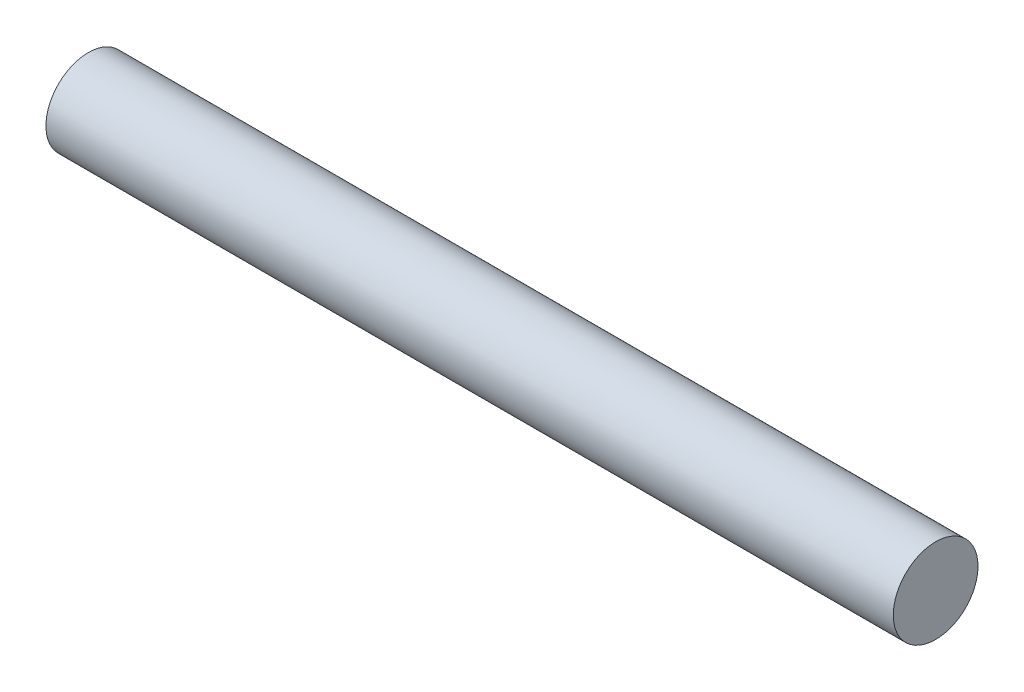
SolidWorks part; units mm, degrees
material "Stainless Steel (ferritic)"
ref_plane "Front Plane" through (0, 0, 0) normal (0, 0, 1) x (1, 0, 0)
ref_plane "Top Plane" through (0, 0, 0) normal (0, 1, 0) x (1, 0, 0)
ref_plane "Right Plane" through (0, 0, 0) normal (1, 0, 0) x (0, 0, -1)
sketch "Sketch1" plane through (0, 0, 0) normal (1, 0, 0) x (0, 0, -1)
  circle A0 centre (0, 0) radius 50
extrude "Boss-Extrude1" add sketch "Sketch1" along normal blind 1000
